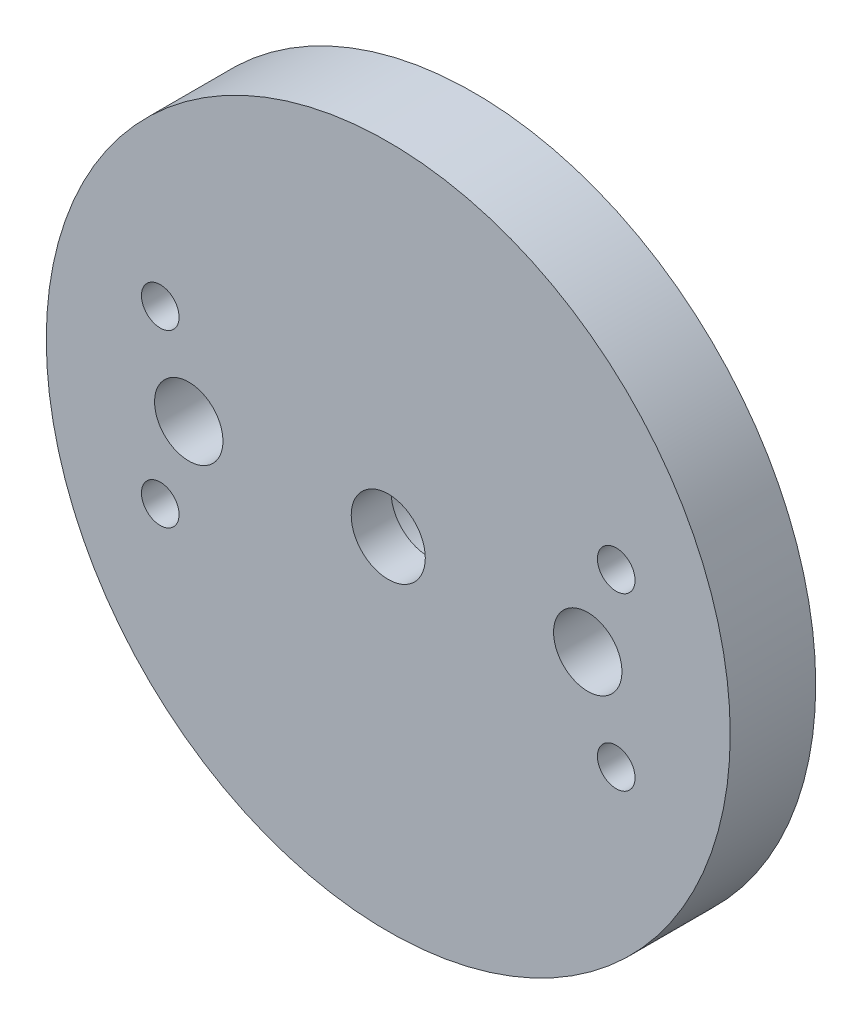
SolidWorks part; units mm, degrees
ref_plane "前视基准面" through (0, 0, 0) normal (0, 0, 1) x (1, 0, 0)
ref_plane "上视基准面" through (0, 0, 0) normal (0, 1, 0) x (1, 0, 0)
ref_plane "右视基准面" through (0, 0, 0) normal (1, 0, 0) x (0, 0, -1)
sketch "草图1" plane through (0, 0, 0) normal (0, 0, 1) x (1, 0, 0)
  circle A0 centre (0, 0) radius 60
  point P0 (0, 0)
  dimension "D1" = 120
extrude "凸台-拉伸1" add sketch "草图1" along normal blind 15
sketch "草图2" plane through (0, 0, 0) normal (0, 0, -1) x (-1, 0, 0)
  line L0 (-60, 0) -> (60, 0) construction
  line L4 (0, 60) -> (0, -60) construction
  circle A0 centre (-35, 0) radius 6
  circle A1 centre (35, 0) radius 6
  circle A2 centre (0, 0) radius 60 construction
  dimension "D2" = 12
  dimension "D3" = 70
extrude "切除-拉伸1" cut sketch "草图2" against normal through all
sketch "草图3" plane through (0, 0, 0) normal (0, 0, -1) x (-1, 0, 0)
  circle A0 centre (0, 0) radius 11
  dimension "D1" = 22
extrude "切除-拉伸2" cut sketch "草图3" against normal blind 8
sketch "草图4" plane through (0, 0, 8) normal (0, 0, -1) x (-1, 0, 0)
  circle A0 centre (0, 0) radius 6.5
  dimension "D1" = 13
extrude "切除-拉伸3" cut sketch "草图4" against normal blind 10
sketch "草图5" plane through (0, 0, 15) normal (0, 0, 1) x (1, 0, 0)
  line L1 (40, 15) -> (-40, 15) construction
  line L2 (40, 15) -> (40, -15) construction
  line L3 (40, -15) -> (-40, -15) construction
  line L4 (-40, 15) -> (-40, -15) construction
  line L5 (40, 15) -> (-40, -15) construction
  line L6 (40, -15) -> (-40, 15) construction
  circle A0 centre (40, 15) radius 3.3
  circle A1 centre (40, -15) radius 3.3
  circle A2 centre (-40, -15) radius 3.3
  circle A3 centre (-40, 15) radius 3.3
  point P0 (0, 0)
  dimension "D1" = 30
  dimension "D2" = 80
extrude "切除-拉伸4" cut sketch "草图5" against normal blind 10
